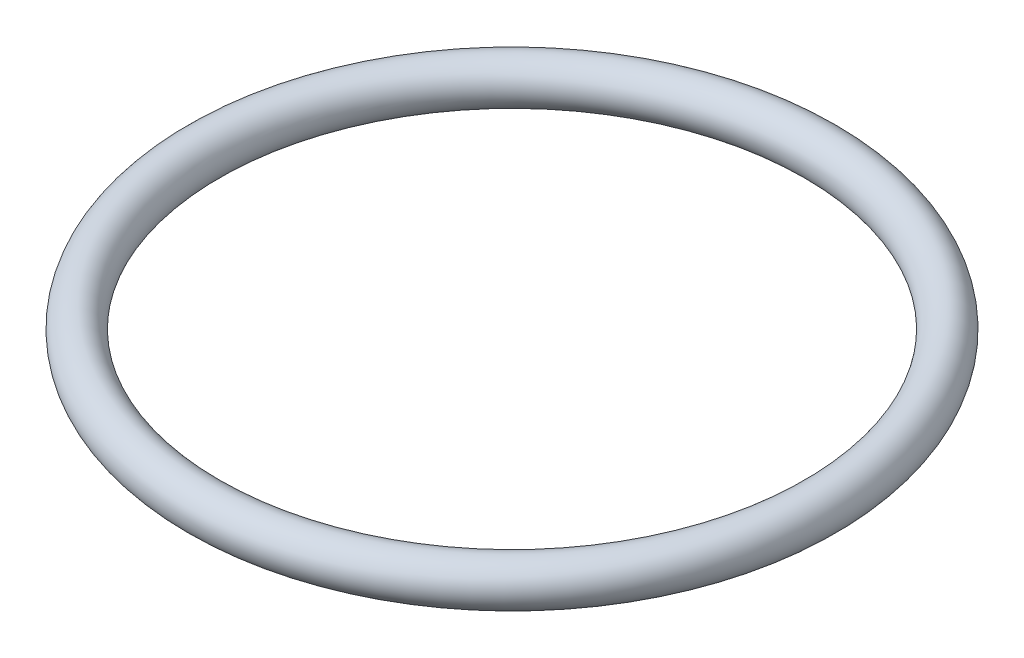
SolidWorks part; units mm, degrees
ref_plane "Front Plane" through (0, 0, 0) normal (0, 0, 1) x (1, 0, 0)
ref_plane "Top Plane" through (0, 0, 0) normal (0, 1, 0) x (1, 0, 0)
ref_plane "Right Plane" through (0, 0, 0) normal (1, 0, 0) x (0, 0, -1)
sketch "Sketch1" plane through (0, 0, 0) normal (1, 0, 0) x (0, 0, -1)
  line L0 (0, -6.8434) -> (0, 8.6434) construction
  circle A0 centre (-12.75, 0) radius 0.9
  dimension "D1" = 1.8
  dimension "D2" = 12.75
revolve "Revolve1" add sketch "Sketch1" angle 360 about L0
sketch "Sketch2" plane through (0, 0, 0) normal (0, 1, 0) x (1, 0, 0)
  line L0 (0, -4.791) -> (0, 14.8312) construction
  line L1 (0, 0) -> (24.2796, 0) construction
  circle A0 centre (0, 0) radius 0.9043
